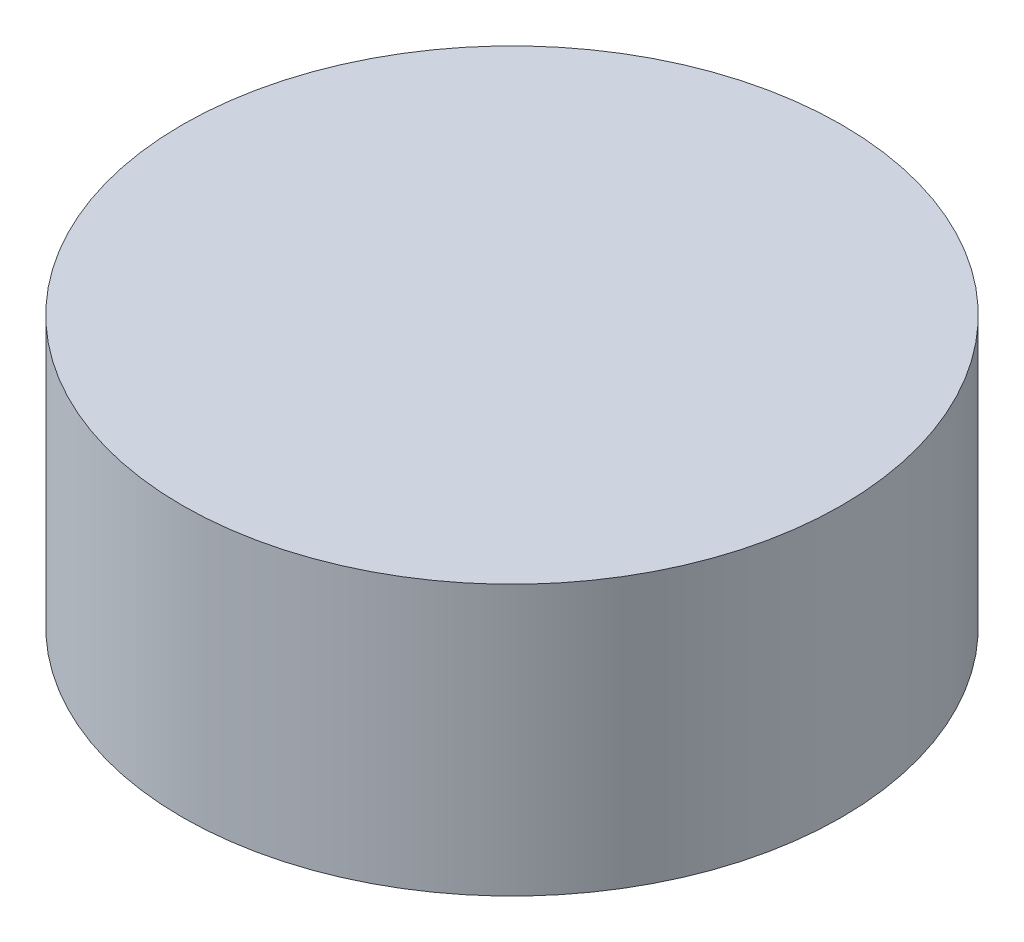
SolidWorks part; units mm, degrees
ref_plane "Front Plane" through (0, 0, 0) normal (0, 0, 1) x (1, 0, 0)
ref_plane "Top Plane" through (0, 0, 0) normal (0, 1, 0) x (1, 0, 0)
ref_plane "Right Plane" through (0, 0, 0) normal (1, 0, 0) x (0, 0, -1)
sketch "Sketch4" plane through (0, 0, 0) normal (0, 0, 1) x (1, 0, 0)
  line L1 (3.1743, 1.9693) -> (8.0578, 1.9693)
  line L2 (3.1743, 1.9693) -> (3.1743, -2.0307)
  line L3 (3.1743, -2.0307) -> (8.0578, -2.0307)
  line L4 (8.0578, 1.9693) -> (8.0578, -2.0307)
  dimension "D1" = 4
revolve "Revolve1" add sketch "Sketch4" angle 360 about L2
